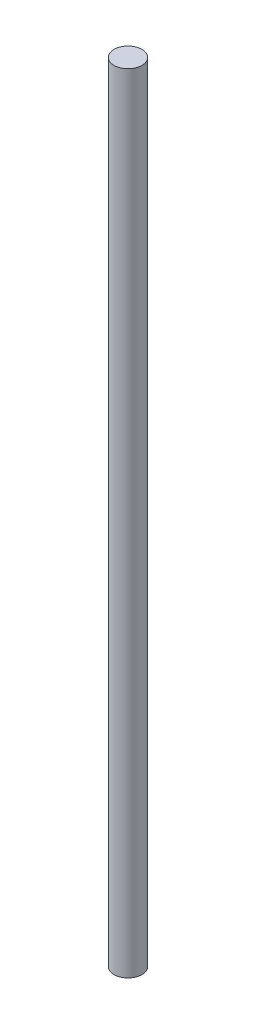
SolidWorks part; units mm, degrees
ref_plane "Front Plane" through (0, 0, 0) normal (0, 0, 1) x (1, 0, 0)
ref_plane "Top Plane" through (0, 0, 0) normal (0, 1, 0) x (1, 0, 0)
ref_plane "Right Plane" through (0, 0, 0) normal (1, 0, 0) x (0, 0, -1)
sketch "Sketch1" plane through (0, 0, 0) normal (0, 1, 0) x (1, 0, 0)
  circle A0 centre (0, 0) radius 12.5
  dimension "D1" = 25
extrude "Boss-Extrude1" add sketch "Sketch1" along normal blind 706.744
